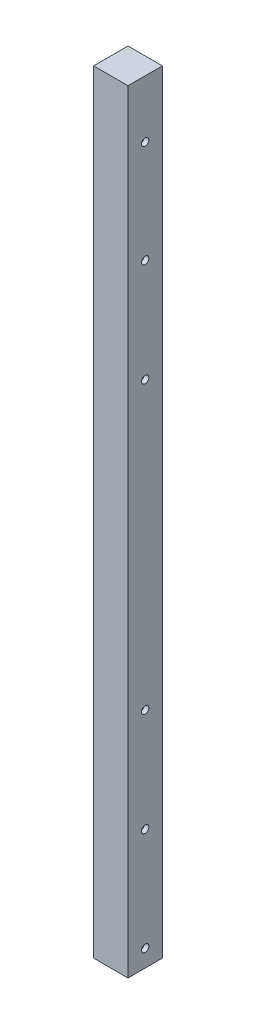
SolidWorks part; units mm, degrees
ref_plane "Front Plane" through (0, 0, 0) normal (0, 0, 1) x (1, 0, 0)
ref_plane "Top Plane" through (0, 0, 0) normal (0, 1, 0) x (1, 0, 0)
ref_plane "Right Plane" through (0, 0, 0) normal (1, 0, 0) x (0, 0, -1)
sketch "Sketch1" plane through (0, 0, 0) normal (0, 1, 0) x (1, 0, 0)
  line L0 (2, 2) -> (2, 13)
  line L1 (0, 0) -> (15, 0)
  line L2 (0, 0) -> (0, 15)
  line L3 (0, 15) -> (15, 15)
  line L4 (15, 0) -> (15, 15)
  line L5 (2, 13) -> (13, 13)
  line L6 (13, 2) -> (13, 13)
  line L7 (2, 2) -> (13, 2)
  dimension "D1" = 15
  dimension "D2" = 2
extrude "Boss-Extrude1" add sketch "Sketch1" along normal blind 337
sketch "Sketch2" plane through (15, 0, 0) normal (1, 0, 0) x (0, 0, -1)
  line L0 (15, 337) -> (0, 332.9808)
  line L1 (0, 337) -> (0, 0) construction
  line L2 (0, 332.9808) -> (0, 337)
  line L3 (0, 337) -> (15, 337)
  dimension "D1" = 15
extrude "Cut-Extrude1" cut sketch "Sketch2" against normal through all
sketch "Sketch3" plane through (0, 0, 0) normal (-1, 0, 0) x (0, 0, 1)
  line L0 (-7.5, 337) -> (-7.5, 0) construction
  line L2 (-15, 0) -> (0, 0) construction
  circle A0 centre (-7.5, 7.5) radius 1.6
  circle A1 centre (-7.5, 312) radius 1.6
  circle A2 centre (-7.5, 267.3) radius 1.6
  circle A3 centre (-7.5, 52.5) radius 1.6
  circle A4 centre (-7.5, 97.5) radius 1.6
  circle A5 centre (-7.5, 222.3) radius 1.6
  point P2 (0, 0)
  point P18 (0, 0)
  dimension "D1" = 3.2
  dimension "D3" = 44.7
  dimension "D4" = 7.5
  dimension "D5" = 45
  dimension "D6" = 45
  dimension "D7" = 45
  dimension "D2" = 124.8
extrude "Cut-Extrude2" cut sketch "Sketch3" against normal through all
sketch "Sketch4" plane through (0, 0, 0) normal (-1, 0, 0) x (0, 0, 1)
  line L0 (-15, 337) -> (0, 337)
  line L1 (0, 337) -> (0, 332.9808)
  line L2 (0, 332.9808) -> (-15, 337)
  line L3 (0, 332.9808) -> (0, 0) construction
extrude "Boss-Extrude2" add sketch "Sketch4" against normal up to surface (15 mm away) up to face at (15, 7.5, -5.9)
